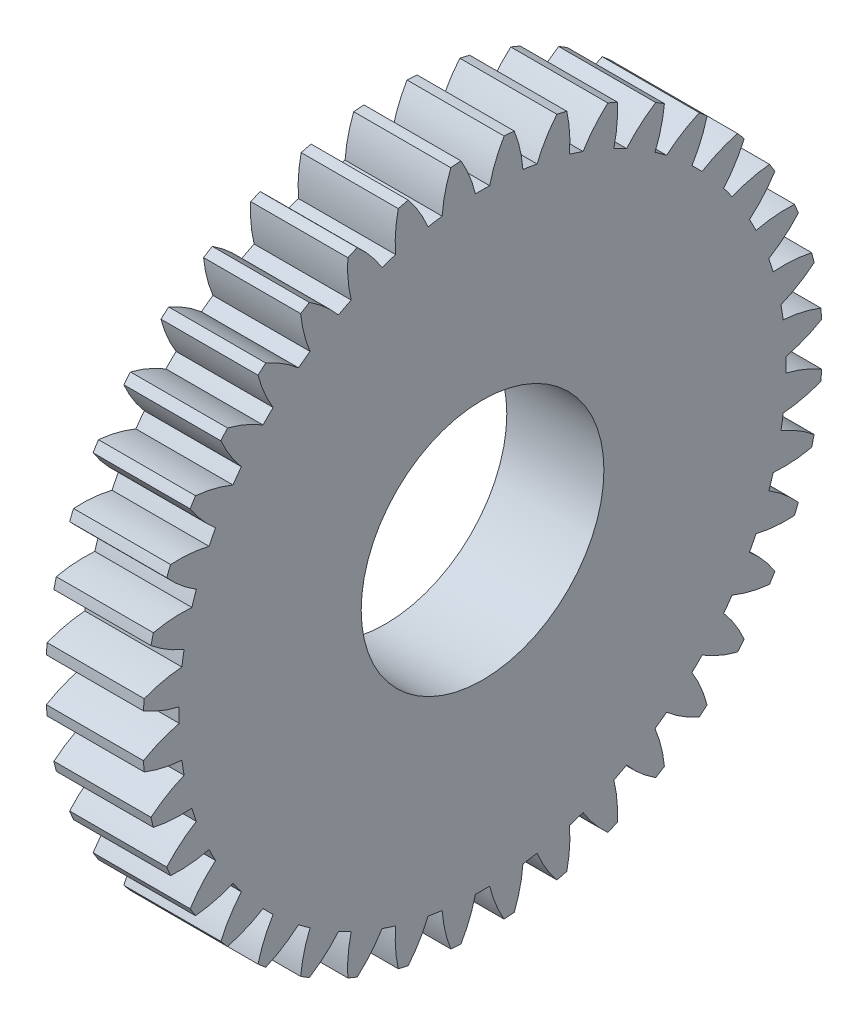
SolidWorks part; units mm, degrees
ref_plane "Plane1" through (0, 0, 0) normal (0, 0, 1) x (1, 0, 0)
ref_plane "Plane2" through (0, 0, 0) normal (0, 1, 0) x (1, 0, 0)
ref_plane "Plane3" through (0, 0, 0) normal (1, 0, 0) x (0, 0, -1)
sketch "HoldingSke" plane through (0, 0, 0) normal (0, 1, 0) x (1, 0, 0)
  line L0 (0, 0) -> (0.383, -0.3214)
  line L1 (-15, 0) -> (100, 0) construction
  line L2 (0, 0) -> (-2.1039, 2.3779)
  line L3 (0, 0) -> (-11.863, 4.5341)
  line L4 (0, 0) -> (6.6156, 5.5511)
  line L5 (0, 0) -> (-46.8476, -17.4728)
  line L6 (0, 0) -> (-9.9476, -6.7116)
  line L7 (-2.1039, 2.3779) -> (8.6586, 51.2059)
  line L8 (-76.2, 54.61) -> (-72.9, 54.61)
  line L9 (-71.009, 38.7566) -> (-53.1078, 45.2721)
  line L10 (-76.2, 71.12) -> (104.1128, 71.12)
  line L11 (0, 0) -> (-12, 0)
  line L12 (-76.2, 101.6) -> (-76.133, 101.6)
  line L13 (24.9733, 27.94) -> (52.9518, 28.4284)
  line L14 (24.9733, 27.94) -> (24.9743, 27.94)
  line L15 (24.9733, 27.94) -> (100.4006, 29.5858)
  line L16 (-63.627, -2) -> (-12.827, -2)
  circle A0 centre (0, 0) radius 15
  circle A1 centre (0, 0) radius 37.499
  circle A2 centre (0, 0) radius 37.5
  circle A3 centre (0, 0) radius 15
  dimension "MHD" = 74.998
  dimension "Hub_dia" = 75
  dimension "Bore" = 30
  dimension "MBD" = 30
  dimension "Num_teeth" = 40
  dimension "Pitch" = 0.5
  dimension "Overall_len" = 50
  dimension "Show_teeth" = 40
  dimension "Thickness" = 12
  dimension "OAL" = 50.0001
  dimension "T_dim" = 3.3
  dimension "Ap" = 20
  dimension "H" = 19.05
  dimension "Pitch_radius" = 180.3128
  dimension "Width" = 12
  dimension "Backlash" = 0.067
  dimension "Addendum_fac" = 1
  dimension "Dedendum_fac" = 1.25
  dimension "Clearance_fac" = 0.25
  dimension "Dedendum_add" = 0.001
  dimension "Module" = 2
sketch "BasProSke" plane through (0, 0, 0) normal (0, 1, 0) x (1, 0, 0)
  line L0 (-10, 0) -> (60, 0) construction
  line L1 (0, 0) -> (0, 42)
  line L2 (0, 0) -> (12, 0)
  line L3 (12, 0) -> (12, 42)
  line L4 (12, 42) -> (0, 42)
  dimension "Thickness" = 12
  dimension "Diameter" = 84
revolve "Base-Revolve" add sketch "BasProSke" angle 360 about L0
sketch "TooCutSke" plane through (0, 0, 0) normal (1, 0, 0) x (0, 0, -1)
  line L1 (0, 0) -> (0, 107) construction
  line L2 (0, 0) -> (-1.6876, 39.9644) construction
  line L3 (0, 0) -> (-6.2726, 79.7007) construction
  line L4 (-1.6876, 39.9644) -> (-3.1363, 39.8504) construction
  arc A0 (0.8828, 37.4886) -> (-0.8828, 37.4886) centre (0, 0) ccw
  arc A1 (2.6784, 41.94) -> (-2.6784, 41.94) centre (0, 0) ccw
  circle A2 centre (0, 0) radius 40 construction
  circle A3 centre (0, 0) radius 37.5877 construction
  arc A4 (-0.8828, 37.4886) -> (-2.6784, 41.94) centre (-16.451, 33.7965) ccw
  arc A5 (2.6784, 41.94) -> (0.8828, 37.4886) centre (16.451, 33.7965) ccw
  dimension "Root_dia" = 74.998
  dimension "Overcut_dia" = 84.0508
  dimension "Pitch_dia" = 80
  dimension "Base_dia" = 75.1754
  dimension "Flank_rad" = 16
  dimension "Half_ang" = 4.5
  dimension "Half_CT" = 1.4531
extrude "ToothCut" cut sketch "TooCutSke" along normal through all
fillet "Breaks" [suppressed] radius 0.04
fillet "RootFillets" [suppressed] radius 0.501
pattern_circular "TeethCuts" count 40 every 9 about axis through (-10, 0, 0) along (1, 0, 0) of "ToothCut", "RootFillets", "Breaks"
sketch "HubNeaOneSke" plane through (0, 0, 0) normal (-1, 0, 0) x (0, 0, 1)
  circle A0 centre (0, 0) radius 37.499
  dimension "Diameter" = 74.998
extrude "HubNearOne" [suppressed] add sketch "HubNeaOneSke" along normal blind 38.0001
sketch "HubNeaBotSke" plane through (0, 0, 0) normal (-1, 0, 0) x (0, 0, 1)
  circle A0 centre (0, 0) radius 37.499
  dimension "Diameter" = 74.998
extrude "HubNearBoth" [suppressed] add sketch "HubNeaBotSke" along normal blind 19
ref_plane "FarPln" through (12, 0, 0) normal (1, 0, 0) x (0, 0, -1)
sketch "HubFarSke" plane through (12, 0, 0) normal (1, 0, 0) x (0, 0, -1)
  circle A0 centre (0, 0) radius 37.499
  dimension "Diameter" = 74.998
extrude "HubFar" [suppressed] add sketch "HubFarSke" along normal blind 19
sketch "BorSke" plane through (0, 0, 0) normal (1, 0, 0) x (0, 0, -1)
  circle A0 centre (0, 0) radius 15
  dimension "Diameter" = 30
extrude "Bore" cut sketch "BorSke" along normal mid plane 100.0001
sketch "KeySke" plane through (0, 0, 0) normal (1, 0, 0) x (0, 0, -1)
  line L0 (-5, 0) -> (-5, 18.3)
  line L1 (-5, 18.3) -> (5, 18.3)
  line L2 (5, 18.3) -> (5, 0)
  line L3 (0, 0) -> (0, 34) construction
  line L4 (-5, 0) -> (5, 0)
  dimension "Offset" = 18.3
  dimension "Width" = 10
extrude "Keyway" [suppressed] cut sketch "KeySke" along normal mid plane 100.0001
pattern_circular "Keyway2" [suppressed] count 2 every 90 about axis through (-10, 0, 0) along (1, 0, 0)
equation "' \"Module@HoldingSke\" = 6.35"
equation "' \"Num_teeth@HoldingSke\" = 12"
equation "' \"Ap@HoldingSke\" =  20"
equation "' \"Ap@HoldingSke\" = 20"
equation "' \"Width@HoldingSke\" = 0.5 * 25.4"
equation "' \"Hub_dia@HoldingSke\"= 1 * 25.4"
equation "' \"Hub_dia@HoldingSke\" = 1 * 25.4"
equation "' \"Overall_len@HoldingSke\" = 1.0 * 25.4"
equation "' \"Bore@HoldingSke\" = 0.75 * 25.4"
equation "' \"T_dim@HoldingSke\" = 0.1 * 25.4"
equation "' \"Width@KeySke\" = 0.25 * 25.4"
equation "' \"Show_teeth@HoldingSke\" = 13"
equation "' \"Backlash@HoldingSke\" = 0.009 * 25.4"
equation "' \"Addendum_fac@HoldingSke\" = 1.0"
equation "' \"Dedendum_fac@HoldingSke\" = 1.25"
equation "' \"Dedendum_add@HoldingSke\" = 0.00005 * 25.4"
equation "' \"Clearance_fac@HoldingSke\" = 0.25"
equation "\"Pitch@HoldingSke\" = 1 / \"Module@HoldingSke\""
equation "\"Overcut_dia@TooCutSke\" = (\"Num_teeth@HoldingSke\" + 2 * \"Addendum_fac@HoldingSke\") / \"Pitch@HoldingSke\" + 0.002 * 25.4"
equation "\"Pitch_dia@TooCutSke\" = \"Num_teeth@HoldingSke\" / \"Pitch@HoldingSke\""
equation "\"Base_dia@TooCutSke\" = \"Num_teeth@HoldingSke\" / \"Pitch@HoldingSke\" * cos((\"Ap@HoldingSke\"  * 3.14159265 / 180))"
equation "\"Root_dia@TooCutSke\" = (\"Num_teeth@HoldingSke\" + 2) / \"Pitch@HoldingSke\" - 2 * (\"Addendum_fac@HoldingSke\" + \"Dedendum_fac@HoldingSke\") / \"Pitch@HoldingSke\" - \"Dedendum_add@HoldingSke\" * 2"
equation "\"Half_ang@TooCutSke\" = 180 / \"Num_teeth@HoldingSke\""
equation "\"Half_CT@TooCutSke\" = \"Num_teeth@HoldingSke\" / \"Pitch@HoldingSke\" * sin((3.14159265 / 2 / \"Num_teeth@HoldingSke\")) / 2 - 7 * \"Backlash@HoldingSke\" / 4"
equation "\"Flank_rad@TooCutSke\" = \"Num_teeth@HoldingSke\" / \"Pitch@HoldingSke\" / 5"
equation "\"Radius@RootFillets\" = \"Clearance_fac@HoldingSke\" / \"Pitch@HoldingSke\" + \"Dedendum_add@HoldingSke\""
equation "\"Break_rad@Breaks\" = 0.02 / \"Pitch@HoldingSke\""
equation "\"Thickness@HoldingSke\" = \"Width@HoldingSke\""
equation "\"OAL@HoldingSke\" = \"Thickness@HoldingSke\""
equation "\"MHD@HoldingSke\" = (\"Num_teeth@HoldingSke\" + 2) / \"Pitch@HoldingSke\" - 2 * (\"Addendum_fac@HoldingSke\" + \"Dedendum_fac@HoldingSke\")  / \"Pitch@HoldingSke\" - \"Dedendum_add@HoldingSke\" * 2"
equation "\"MBD@HoldingSke\" = (\"Num_teeth@HoldingSke\" + 2) / \"Pitch@HoldingSke\" - 2 * (\"Addendum_fac@HoldingSke\" + \"Dedendum_fac@HoldingSke\")  / \"Pitch@HoldingSke\" - \"Dedendum_add@HoldingSke\" * 2 - 0.002 * 25.4"
equation "\"MHD@HoldingSke\" = ((sgn( \"MHD@HoldingSke\" - \"Hub_dia@HoldingSke\" )-1)*( \"MHD@HoldingSke\" - \"Hub_dia@HoldingSke\" ))/-2+ \"Hub_dia@HoldingSke\""
equation "\"MBD@HoldingSke\" = ((sgn( \"MBD@HoldingSke\" - \"Bore@HoldingSke\" )-1)*( \"MBD@HoldingSke\" - \"Bore@HoldingSke\" ))/-2+ \"Bore@HoldingSke\""
equation "\"OAL@HoldingSke\" = ((sgn( \"OAL@HoldingSke\" - \"Overall_len@HoldingSke\" )+1)*( \"OAL@HoldingSke\" - \"Overall_len@HoldingSke\" ))/2 + \"Overall_len@HoldingSke\" + 0.000002 * 25.4"
equation "\"Num_teeth@TeethCuts\" = int( \"Show_teeth@HoldingSke\" ) + 1"
equation "\"Num_teeth@TeethCuts\" = ((sgn( \"Num_teeth@TeethCuts\" - \"Num_teeth@HoldingSke\" )-1)*( \"Num_teeth@TeethCuts\" - \"Num_teeth@HoldingSke\" ))/-2+ \"Num_teeth@HoldingSke\""
equation "\"Num_teeth@TeethCuts\" = ((sgn( \"Num_teeth@TeethCuts\" - 2.0)+1)*( \"Num_teeth@TeethCuts\" - 2.0))/2 +2.0"
equation "\"Angle@TeethCuts\" = 360.0 / \"Num_teeth@HoldingSke\""
equation "\"Diameter@BasProSke\" = (\"Num_teeth@HoldingSke\" + 2 * \"Addendum_fac@HoldingSke\") / \"Pitch@HoldingSke\""
equation "\"Thickness@BasProSke\"  = \"Thickness@HoldingSke\""
equation "' \"Fillet_rad@BasProSke\" =  \"Thickness@HoldingSke\" * 0.05"
equation "' \"Fillet_rad@BasProSke\" = \"Thickness@HoldingSke\" * 0.05"
equation "\"MHD@HoldingSke\" = ((sgn( \"MHD@HoldingSke\" - \"Root_dia@TooCutSke\" )-1)*( \"MHD@HoldingSke\" - \"Root_dia@TooCutSke\" ))/-2+ \"Root_dia@TooCutSke\""
equation "\"Diameter@HubNeaOneSke\" = \"MHD@HoldingSke\""
equation "\"Length@HubNearOne\" = \"OAL@HoldingSke\" - \"Thickness@BasProSke\""
equation "\"Diameter@HubNeaBotSke\" = \"MHD@HoldingSke\""
equation "\"Length@HubNearBoth\" = ( \"OAL@HoldingSke\" - \"Thickness@BasProSke\" ) / 2.0"
equation "\"Thickness@FarPln\" = \"Thickness@BasProSke\""
equation "\"Diameter@HubFarSke\" = \"MHD@HoldingSke\""
equation "\"Length@HubFar\" = ( \"OAL@HoldingSke\" - \"Thickness@BasProSke\" ) / 2.0"
equation "\"Diameter@BorSke\" = \"MBD@HoldingSke\""
equation "\"D1@Bore\" = \"OAL@HoldingSke\" * 2.0"
equation "\"D1@Keyway\" = \"OAL@HoldingSke\" * 2.0"
equation "\"Offset@KeySke\" = \"T_dim@HoldingSke\" + \"MBD@HoldingSke\" / 2.0"
